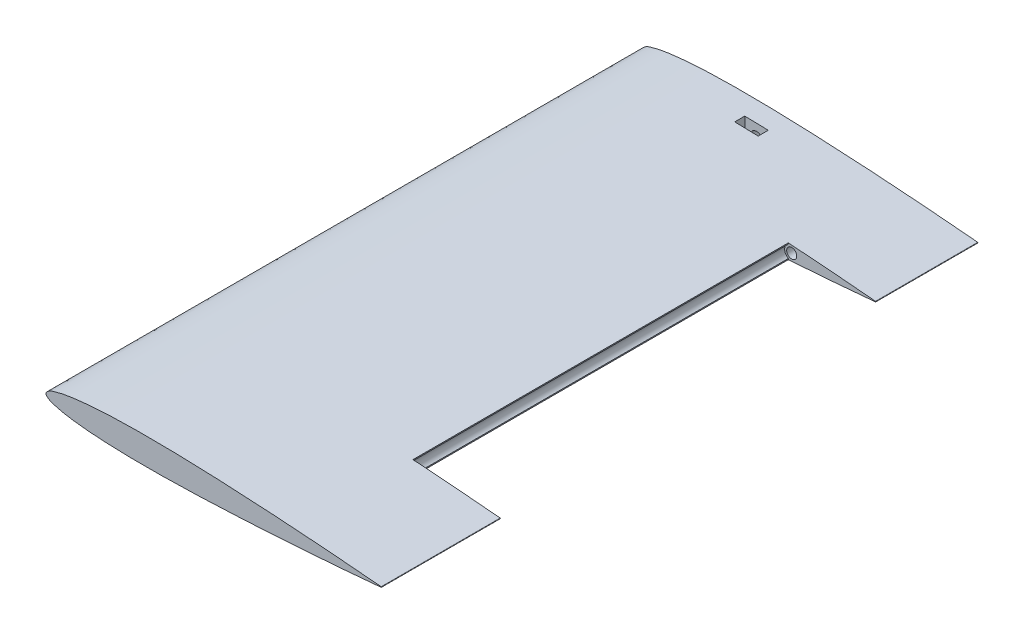
SolidWorks part; units mm, degrees
material "ABS generico"
ref_plane "Piano frontale" through (0, 0, 0) normal (0, 0, 1) x (1, 0, 0)
ref_plane "Piano superiore" through (0, 0, 0) normal (0, 1, 0) x (1, 0, 0)
ref_plane "Piano destro" through (0, 0, 0) normal (1, 0, 0) x (0, 0, -1)
curve "ProfiloBase"
  spline degree 3 poles (100, 0.084, 0) (98.3335, 0.2367, 0) (95.0012, 0.5422, 0) (88.3356, 1.1109, 0) (80.0033, 1.7636, 0) (70.003, 2.4579, 0) (60.0031, 3.0617, 0) (50.003, 3.5521, 0) (40.0026, 3.9029, 0) (31.667, 4.0253, 0) (24.9992, 3.9769, 0) (19.9978, 3.845, 0) (14.9934, 3.5925, 0) (10.8272, 3.2377, 0) (7.4891, 2.814, 0) (4.9936, 2.4037, 0) (2.8496, 1.8679, 0) (1.1654, 1.321, 0) (-0.6646, 0, 0) (1.1654, -1.321, 0) (2.8496, -1.8679, 0) (4.9936, -2.4037, 0) (7.4891, -2.814, 0) (10.8272, -3.2377, 0) (14.9934, -3.5925, 0) (19.9978, -3.845, 0) (24.9992, -3.9769, 0) (31.667, -4.0253, 0) (40.0026, -3.9029, 0) (50.003, -3.5521, 0) (60.0031, -3.0617, 0) (70.003, -2.4579, 0) (80.0033, -1.7636, 0) (88.3356, -1.1109, 0) (95.0012, -0.5422, 0) (98.3335, -0.2367, 0) (100, -0.084, 0) knots 0 0 0 0 0.024876 0.049742 0.099443 0.149112 0.198751 0.248359 0.297937 0.347491 0.372267 0.397051 0.421859 0.446731 0.45922 0.471791 0.48456 0.491195 0.5 0.508805 0.51544 0.528209 0.54078 0.553269 0.578141 0.602949 0.627733 0.652509 0.702063 0.751641 0.801249 0.850888 0.900557 0.950258 0.975124 1 1 1 1
sketch "Schizzo1" plane through (0, 0, 0) normal (0, 0, 1) x (1, 0, 0)
  line L0 (100, 0.084) -> (100, -0.084) construction
  arc A0 (100, 0.084) -> (100, -0.084) centre (100, 0) cw
  spline S0 degree 3 poles (1490.7083, 8861.9983) (489.6178, -110.9206) (294.0791, -16.4436) (88.3356, 1.1109) (80.0033, 1.7636) (70.003, 2.4579) (60.0031, 3.0617) (50.003, 3.5521) (40.0026, 3.9029) (31.667, 4.0253) (24.9992, 3.9769) (19.9978, 3.845) (14.9934, 3.5925) (10.8272, 3.2377) (7.4891, 2.814) (4.9936, 2.4037) (2.8496, 1.8679) (1.1654, 1.321) (-0.6646, 0) (1.1654, -1.321) (2.8496, -1.8679) (4.9936, -2.4037) (7.4891, -2.814) (10.8272, -3.2377) (14.9934, -3.5925) (19.9978, -3.845) (24.9992, -3.9769) (31.667, -4.0253) (40.0026, -3.9029) (50.003, -3.5521) (60.0031, -3.0617) (70.003, -2.4579) (80.0033, -1.7636) (88.3356, -1.1109) (294.0785, 16.4435) (489.6166, 110.92) (1490.6994, -8861.9185) knots -2.970007 -2.970007 -2.970007 -2.970007 0.024876 0.049742 0.099443 0.149112 0.198751 0.248359 0.297937 0.347491 0.372267 0.397051 0.421859 0.446731 0.45922 0.471791 0.48456 0.491195 0.5 0.508805 0.51544 0.528209 0.54078 0.553269 0.578141 0.602949 0.627733 0.652509 0.702063 0.751641 0.801249 0.850888 0.900557 0.950258 0.975124 3.969998 3.969998 3.969998 3.969998 only from (100, 0.084) to (100, -0.084) construction
  spline S1 degree 3 poles (100, 0.084) (98.3335, 0.2367) (95.0012, 0.5422) (88.3356, 1.1109) (80.0033, 1.7636) (70.003, 2.4579) (60.0031, 3.0617) (50.003, 3.5521) (40.0026, 3.9029) (31.667, 4.0253) (24.9992, 3.9769) (19.9978, 3.845) (14.9934, 3.5925) (10.8272, 3.2377) (7.4891, 2.814) (4.9936, 2.4037) (2.8496, 1.8679) (1.1654, 1.321) (-0.6646, 0) (1.1654, -1.321) (2.8496, -1.8679) (4.9936, -2.4037) (7.4891, -2.814) (10.8272, -3.2377) (14.9934, -3.5925) (19.9978, -3.845) (24.9992, -3.9769) (31.667, -4.0253) (40.0026, -3.9029) (50.003, -3.5521) (60.0031, -3.0617) (70.003, -2.4579) (80.0033, -1.7636) (88.3356, -1.1109) (95.0012, -0.5422) (98.3335, -0.2367) (100, -0.084) knots 0 0 0 0 0.024876 0.049742 0.099443 0.149112 0.198751 0.248359 0.297937 0.347491 0.372267 0.397051 0.421859 0.446731 0.45922 0.471791 0.48456 0.491195 0.5 0.508805 0.51544 0.528209 0.54078 0.553269 0.578141 0.602949 0.627733 0.652509 0.702063 0.751641 0.801249 0.850888 0.900557 0.950258 0.975124 1 1 1 1
  point P5 (100, 0)
extrude "FoamBassa" add sketch "Schizzo1" along normal blind 30.5
sketch "Schizzo2" plane through (0, 0, 30.5) normal (0, 0, 1) x (1, 0, 0)
  line L0 (75, 2.1072) -> (75, -2.1072) construction
  arc A4 (75, 2.1072) -> (75, -2.1072) centre (75, 0) ccw
  spline S1 degree 3 poles (774.5938, 2905.893) (370.1816, -60.6448) (232.5901, -11.1972) (88.3356, 1.1109) (80.0033, 1.7636) (70.003, 2.4579) (60.0031, 3.0617) (50.003, 3.5521) (40.0026, 3.9029) (31.667, 4.0253) (24.9992, 3.9769) (19.9978, 3.845) (14.9934, 3.5925) (10.8272, 3.2377) (7.4891, 2.814) (4.9936, 2.4037) (2.8496, 1.8679) (1.1654, 1.321) (-0.6646, 0) (1.1654, -1.321) (2.8496, -1.8679) (4.9936, -2.4037) (7.4891, -2.814) (10.8272, -3.2377) (14.9934, -3.5925) (19.9978, -3.845) (24.9992, -3.9769) (31.667, -4.0253) (40.0026, -3.9029) (50.003, -3.5521) (60.0031, -3.0617) (70.003, -2.4579) (80.0033, -1.7636) (88.3356, -1.1109) (232.5893, 11.1971) (370.1799, 60.6442) (774.5865, -2905.8392) knots -2.052665 -2.052665 -2.052665 -2.052665 0.024876 0.049742 0.099443 0.149112 0.198751 0.248359 0.297937 0.347491 0.372267 0.397051 0.421859 0.446731 0.45922 0.471791 0.48456 0.491195 0.5 0.508805 0.51544 0.528209 0.54078 0.553269 0.578141 0.602949 0.627733 0.652509 0.702063 0.751641 0.801249 0.850888 0.900557 0.950258 0.975124 3.052652 3.052652 3.052652 3.052652 only from (100, 0.084) to (100, -0.084) construction
  spline S2 degree 3 poles (75, 2.1072) (73.3336, 2.2229) (68.3351, 2.5586) (60.0031, 3.0617) (50.003, 3.5521) (40.0026, 3.9029) (31.667, 4.0253) (24.9992, 3.9769) (19.9978, 3.845) (14.9934, 3.5925) (10.8272, 3.2377) (7.4891, 2.814) (4.9936, 2.4037) (2.8496, 1.8679) (1.1654, 1.321) (-0.6646, 0) (1.1654, -1.321) (2.8496, -1.8679) (4.9936, -2.4037) (7.4891, -2.814) (10.8272, -3.2377) (14.9934, -3.5925) (19.9978, -3.845) (24.9992, -3.9769) (31.667, -4.0253) (40.0026, -3.9029) (50.003, -3.5521) (60.0031, -3.0617) (68.3351, -2.5586) (73.3336, -2.2229) (75, -2.1072) knots 0.124282 0.124282 0.124282 0.124282 0.149112 0.198751 0.248359 0.297937 0.347491 0.372267 0.397051 0.421859 0.446731 0.45922 0.471791 0.48456 0.491195 0.5 0.508805 0.51544 0.528209 0.54078 0.553269 0.578141 0.602949 0.627733 0.652509 0.702063 0.751641 0.801249 0.850888 0.875718 0.875718 0.875718 0.875718
  dimension "D1" = 4.2144
extrude "FoamMedia" add sketch "Schizzo2" along normal blind 112
sketch "Schizzo4" plane through (0, 0, 142.5) normal (0, 0, 1) x (1, 0, 0)
  line L1 (75, 2.1762) -> (74, 2.1762)
  line L2 (75, 2.1762) -> (75, -2.1762)
  line L3 (75, -2.1762) -> (74, -2.1762)
  line L4 (74, 2.1762) -> (74, -2.1762)
  spline S0 degree 3 poles (75, 2.1072) (73.3336, 2.2229) (68.3351, 2.5586) (60.0031, 3.0617) (50.003, 3.5521) (40.0026, 3.9029) (31.667, 4.0253) (24.9992, 3.9769) (19.9978, 3.845) (14.9934, 3.5925) (10.8272, 3.2377) (7.4891, 2.814) (4.9936, 2.4037) (2.8496, 1.8679) (1.1654, 1.321) (-0.6646, 0) (1.1654, -1.321) (2.8496, -1.8679) (4.9936, -2.4037) (7.4891, -2.814) (10.8272, -3.2377) (14.9934, -3.5925) (19.9978, -3.845) (24.9992, -3.9769) (31.667, -4.0253) (40.0026, -3.9029) (50.003, -3.5521) (60.0031, -3.0617) (68.3351, -2.5586) (73.3336, -2.2229) (75, -2.1072) knots 0.124282 0.124282 0.124282 0.124282 0.149112 0.198751 0.248359 0.297937 0.347491 0.372267 0.397051 0.421859 0.446731 0.45922 0.471791 0.48456 0.491195 0.5 0.508805 0.51544 0.528209 0.54078 0.553269 0.578141 0.602949 0.627733 0.652509 0.702063 0.751641 0.801249 0.850888 0.875718 0.875718 0.875718 0.875718 construction
  dimension "D1" = 1
extrude "SmussoParteMobile" cut sketch "Schizzo4" against normal up to surface (112 mm away) up to face at (86.9942, -0.5058, 30.5)
sketch "Schizzo6" plane through (0, 0, 142.5) normal (0, 0, 1) x (1, 0, 0)
  arc A0 (100, 0.084) -> (100, -0.084) centre (100, 0) cw
  spline S0 degree 3 poles (633.0503, 1915.9881) (335.6221, -48.8321) (214.9188, -9.6895) (88.3356, 1.1109) (80.0033, 1.7636) (70.003, 2.4579) (60.0031, 3.0617) (50.003, 3.5521) (40.0026, 3.9029) (31.667, 4.0253) (24.9992, 3.9769) (19.9978, 3.845) (14.9934, 3.5925) (10.8272, 3.2377) (7.4891, 2.814) (4.9936, 2.4037) (2.8496, 1.8679) (1.1654, 1.321) (-0.6646, 0) (1.1654, -1.321) (2.8496, -1.8679) (4.9936, -2.4037) (7.4891, -2.814) (10.8272, -3.2377) (14.9934, -3.5925) (19.9978, -3.845) (24.9992, -3.9769) (31.667, -4.0253) (40.0026, -3.9029) (50.003, -3.5521) (60.0031, -3.0617) (70.003, -2.4579) (80.0033, -1.7636) (88.3356, -1.1109) (214.9185, 9.6894) (335.6215, 48.8319) (633.0478, -1915.9718) knots -1.78903 -1.78903 -1.78903 -1.78903 0.024876 0.049742 0.099443 0.149112 0.198751 0.248359 0.297937 0.347491 0.372267 0.397051 0.421859 0.446731 0.45922 0.471791 0.48456 0.491195 0.5 0.508805 0.51544 0.528209 0.54078 0.553269 0.578141 0.602949 0.627733 0.652509 0.702063 0.751641 0.801249 0.850888 0.900557 0.950258 0.975124 2.789025 2.789025 2.789025 2.789025 only from (100, 0.084) to (100, -0.084) construction
  spline S1 degree 3 poles (100, 0.084) (98.3335, 0.2367) (95.0012, 0.5422) (88.3356, 1.1109) (80.0033, 1.7636) (70.003, 2.4579) (60.0031, 3.0617) (50.003, 3.5521) (40.0026, 3.9029) (31.667, 4.0253) (24.9992, 3.9769) (19.9978, 3.845) (14.9934, 3.5925) (10.8272, 3.2377) (7.4891, 2.814) (4.9936, 2.4037) (2.8496, 1.8679) (1.1654, 1.321) (-0.6646, 0) (1.1654, -1.321) (2.8496, -1.8679) (4.9936, -2.4037) (7.4891, -2.814) (10.8272, -3.2377) (14.9934, -3.5925) (19.9978, -3.845) (24.9992, -3.9769) (31.667, -4.0253) (40.0026, -3.9029) (50.003, -3.5521) (60.0031, -3.0617) (70.003, -2.4579) (80.0033, -1.7636) (88.3356, -1.1109) (95.0012, -0.5422) (98.3335, -0.2367) (100, -0.084) knots 0 0 0 0 0.024876 0.049742 0.099443 0.149112 0.198751 0.248359 0.297937 0.347491 0.372267 0.397051 0.421859 0.446731 0.45922 0.471791 0.48456 0.491195 0.5 0.508805 0.51544 0.528209 0.54078 0.553269 0.578141 0.602949 0.627733 0.652509 0.702063 0.751641 0.801249 0.850888 0.900557 0.950258 0.975124 1 1 1 1
extrude "FoamAlta" add sketch "Schizzo6" along normal blind 35.5
sketch "Schizzo5" plane through (0, 0, 30.5) normal (0, 0, 1) x (1, 0, 0)
  circle A0 centre (75, 0) radius 1.5
  dimension "D1" = 3
extrude "ForoPernoRuddevator" cut sketch "Schizzo5" against normal through all and the other way offset from surface (142.5 mm away) 5 other way up to face at (100.042, 0.042, 178)
sketch "Schizzo8" plane through (0, 0, 0) normal (0, 0, -1) x (-1, 0, 0)
  circle A0 centre (-25, 0) radius 3
  dimension "D1" = 6
  dimension "D2" = 25
extrude "ForoLongherone" cut sketch "Schizzo8" against normal blind 173
sketch "Schizzo9" plane through (0, 0, 0) normal (0, 0, -1) x (-1, 0, 0)
  line L1 (-27.6458, 3) -> (-22.3542, 3)
  line L3 (-27.6458, -3) -> (-22.3542, -3)
  arc A0 (-27.6458, 3) -> (-27.6458, -3) centre (-25, 0) ccw
  circle A1 centre (-25, 0) radius 3 construction
  arc A2 (-22.3542, -3) -> (-22.3542, 3) centre (-25, 0) ccw
  dimension "D1" = 8
extrude "AggancioLongherone" cut sketch "Schizzo9" against normal blind 5
sketch "Schizzo10" plane through (0, 0, 0) normal (0, 0, -1) x (-1, 0, 0)
  line L0 (-25, 0) -> (-40, 0) construction
  circle A0 centre (-25, 0) radius 3 construction
  circle A1 centre (-25, 0) radius 3 construction
  circle A2 centre (-40, 0) radius 1.75
  dimension "D2" = 3.5
  dimension "D1" = 15
extrude "ForoViteBase" cut sketch "Schizzo10" against normal blind 13
ref_plane "PianoDado" through (0, 0, 6) normal (0, 0, -1) x (-1, 0, 0)
sketch "Schizzo11" plane through (0, 0, 6) normal (0, 0, -1) x (-1, 0, 0)
  line L0 (-43.5, 0) -> (-43.5, 5)
  line L1 (-41.75, -3.0311) -> (-38.25, -3.0311) construction
  line L2 (-38.25, -3.0311) -> (-36.5, 0) construction
  line L3 (-36.5, 0) -> (-38.25, 3.0311) construction
  line L4 (-38.25, 3.0311) -> (-41.75, 3.0311) construction
  line L5 (-41.75, 3.0311) -> (-43.5, 0) construction
  line L6 (-43.5, 0) -> (-41.75, -3.0311) construction
  line L7 (-36.5, 0) -> (-36.5, 5)
  line L8 (-36.5, 5) -> (-43.5, 5)
  line L9 (-43.5, 0) -> (-41.75, -3.0311)
  line L10 (-41.75, -3.0311) -> (-38.25, -3.0311)
  line L11 (-38.25, -3.0311) -> (-36.5, 0)
  circle A0 centre (-40, 0) radius 3.0311 construction
  dimension "D1" = 3.5
  dimension "D2" = 5
extrude "IntaglioDado" cut sketch "Schizzo11" against normal blind 3
sketch "Schizzo12" plane through (0, 0, 0) normal (0, 1, 0) x (1, 0, 0)
  line L0 (36.5, -9) -> (36.5, -6) construction
  line L1 (31.5, -56) -> (56.5, -56)
  line L2 (31.5, -56) -> (31.5, -20)
  line L3 (31.5, -20) -> (56.5, -20)
  line L4 (56.5, -56) -> (56.5, -20)
  line L5 (43.5, -9) -> (36.5, -9) construction
  dimension "D1" = 36
  dimension "D2" = 25
  dimension "D3" = 5
  dimension "D4" = 11
extrude "IntaglioServomotore" cut sketch "Schizzo12" against normal blind 10 and the other way blind 1
